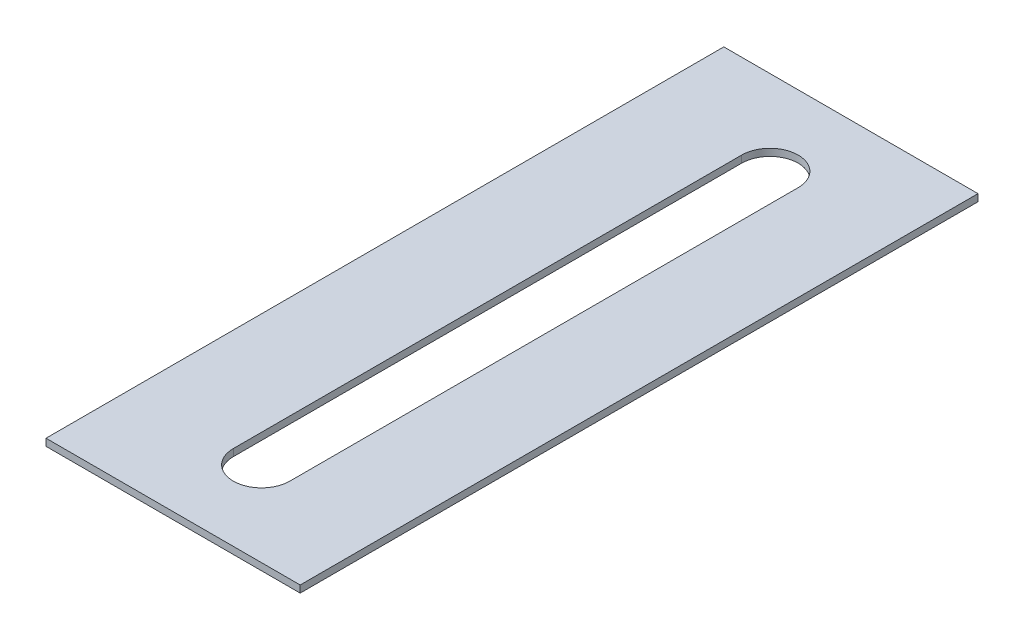
SolidWorks part; units mm, degrees
ref_plane "Front Plane" through (0, 0, 0) normal (0, 0, 1) x (1, 0, 0)
ref_plane "Top Plane" through (0, 0, 0) normal (0, 1, 0) x (1, 0, 0)
ref_plane "Right Plane" through (0, 0, 0) normal (1, 0, 0) x (0, 0, -1)
sketch "Sketch2" plane through (0, 0, 0) normal (0, 1, 0) x (1, 0, 0)
  line L1 (0, 0) -> (-228.6, 0)
  line L2 (0, 0) -> (0, 609.6)
  line L3 (0, 609.6) -> (-228.6, 609.6)
  line L4 (-228.6, 0) -> (-228.6, 609.6)
  dimension "D1" = 609.6
  dimension "D2" = 228.6
extrude "Boss-Extrude1" add sketch "Sketch2" along normal blind 6.35
sketch "Sketch3" plane through (0, 6.35, 0) normal (0, 1, 0) x (1, 0, 0)
  line L0 (-110.9274, 76.2) -> (-110.9274, 533.4) construction
  line L1 (-136.3274, 76.2) -> (-136.3274, 533.4)
  line L2 (-85.5274, 76.2) -> (-85.5274, 533.4)
  line L3 (-110.9274, 609.6) -> (-110.9274, 558.8) construction
  line L6 (0, 609.6) -> (-228.6, 609.6) construction
  line L7 (-110.9274, 558.8) -> (-110.9274, 609.6) construction
  line L8 (-110.9274, 50.8) -> (-110.9274, 0) construction
  line L9 (-228.6, 0) -> (0, 0) construction
  arc A0 (-136.3274, 76.2) -> (-85.5274, 76.2) centre (-110.9274, 76.2) ccw
  arc A1 (-85.5274, 533.4) -> (-136.3274, 533.4) centre (-110.9274, 533.4) ccw
  point P2 (-110.9274, 304.8)
extrude "Cut-Extrude1" cut sketch "Sketch3" against normal blind 6.35 contours L2 A1 L1 A0
